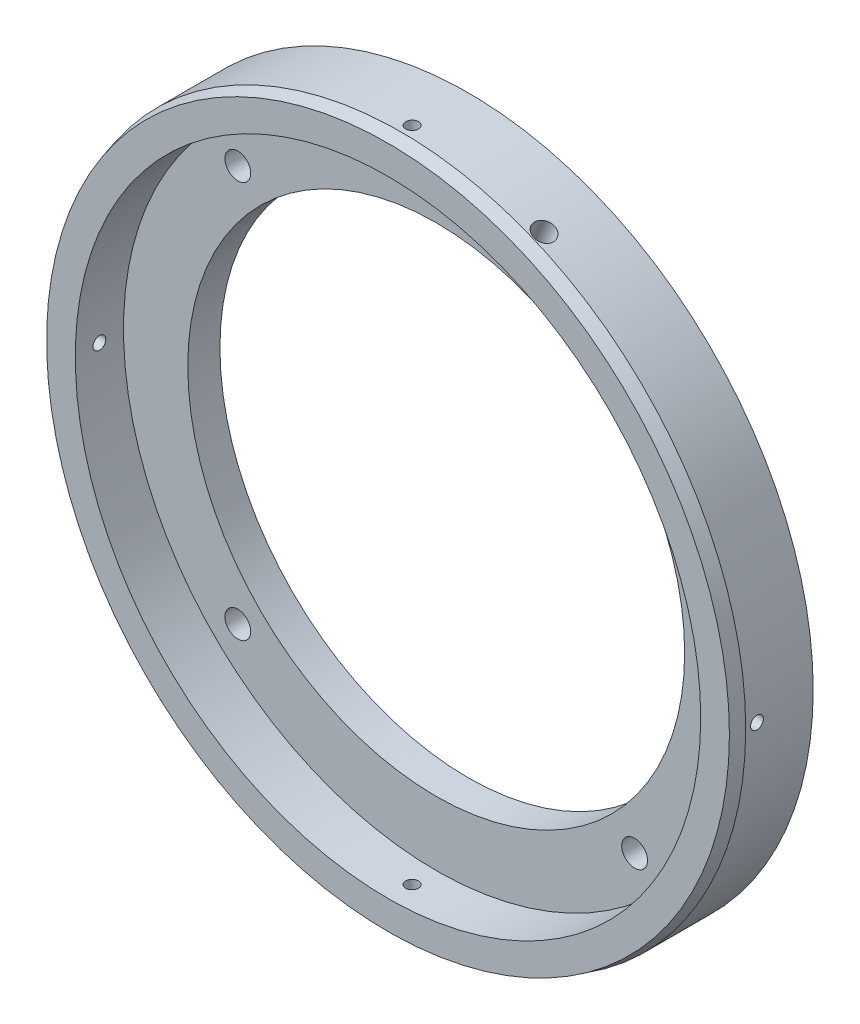
SolidWorks part; units mm, degrees
material "6061-T6 (SS)"
ref_plane "Front Plane" through (0, 0, 0) normal (0, 0, 1) x (1, 0, 0)
ref_plane "Top Plane" through (0, 0, 0) normal (0, 1, 0) x (1, 0, 0)
ref_plane "Right Plane" through (0, 0, 0) normal (1, 0, 0) x (0, 0, -1)
sketch "Sketch1" plane through (0, 0, 0) normal (0, 0, 1) x (1, 0, 0)
  circle A0 centre (0, 0) radius 68.1355
  circle A1 centre (0, 0) radius 49.0855
extrude "Extrude1" add sketch "Sketch1" along normal blind 15.875
sketch "Sketch2" plane through (0, 0, 15.875) normal (0, 0, 1) x (1, 0, 0)
  circle A0 centre (0, 0) radius 61.7855
extrude "Extrude2" cut sketch "Sketch2" against normal blind 9.525
ref_plane "Plane1" through (0, 0, 11.1125) normal (0, 0, 1) x (1, 0, 0)
sketch "Sketch3" plane through (0, 0, 11.1125) normal (0, 0, 1) x (1, 0, 0)
  line L0 (0, 0) -> (0, 68.1355) construction
  line L1 (0, 0) -> (26.0743, 62.949) construction
  circle A0 centre (0, 0) radius 68.1355 construction
  arc A1 (0, 68.1355) -> (26.0743, 62.949) centre (0, 0) cw
  circle A2 centre (0, 0) radius 55.4355
  arc A3 (0, 55.4355) -> (39.1988, 39.1988) centre (0, 0) cw
ref_plane "Plane3" through (26.0743, 62.949, 11.1125) normal (0.3827, 0.9239, 0) x (-0.9239, 0.3827, 0)
hole_wizard "#21 (0.159) Diameter Hole1" positions "Sketch7" profile "Sketch6" hole size "#21" standard "Ansi Inch"
sketch "Sketch7" plane through (26.0743, 62.949, 11.1125) normal (0.3827, 0.9239, 0) x (-0.9239, 0.3827, 0)
  point P1 (0, 0)
sketch "Sketch6" plane through (26.0743, 62.949, 11.1125) normal (0, 0, 1) x (-0.9239, 0.3827, 0)
  line L0 (0, 0) -> (0, 13.9133)
  line L1 (0, 13.9133) -> (2.0193, 12.7)
  line L2 (2.0193, 12.7) -> (2.0193, 0)
  line L5 (2.0193, 0) -> (0, 0)
  line L10 (0, 13.9133) -> (-2.0193, 12.7) construction
  line L11 (0, -6.35) -> (0, 107.95) construction
  dimension "Hole Dia." = 4.0386
  dimension "Hole Depth" = 12.7
  dimension "Drill Angle" = 118
ref_plane "Plane2" through (0, 68.1355, 11.1125) normal (0, 1, 0) x (-1, 0, 0)
hole_wizard "#39 (0.0995) Diameter Hole2" positions "Sketch5" profile "Sketch4" hole size "#39" standard "Ansi Inch"
sketch "Sketch5" plane through (0, 68.1355, 11.1125) normal (0, 1, 0) x (-1, 0, 0)
  point P1 (0, 0)
sketch "Sketch4" plane through (0, 68.1355, 11.1125) normal (1, 0, 0) x (0, 0, 1)
  line L0 (0, 0) -> (0, 13.4593)
  line L1 (0, 13.4593) -> (1.2636, 12.7)
  line L2 (1.2636, 12.7) -> (1.2636, 0)
  line L5 (1.2636, 0) -> (0, 0)
  line L10 (0, 13.4593) -> (-1.2637, 12.7) construction
  line L11 (0, -6.35) -> (0, 107.95) construction
  dimension "Hole Dia." = 2.5273
  dimension "Hole Depth" = 12.7
  dimension "Drill Angle" = 118
pattern_circular "CirPattern1" count 4 over 360 about axis through (0, 0, 15.875) along (0, 0, -1) of "#39 (0.0995) Diameter Hole2"
sketch "Sketch11" plane through (0, 0, 6.35) normal (0, 0, 1) x (1, 0, 0)
  arc A0 (39.1988, 39.1988) -> (46.0929, 30.7983) centre (0, 0) cw construction
  arc A1 (46.0929, 30.7983) -> (51.2157, 21.2142) centre (0, 0) cw construction
hole_wizard "#7 (0.201) Diameter Hole1" positions "Sketch9" profile "Sketch8" hole size "#7" standard "Ansi Inch"
sketch "Sketch9" plane through (0, 0, 11.1125) normal (0, 0, 1) x (1, 0, 0)
  point P1 (39.1988, 39.1988)
sketch "Sketch8" plane through (39.1988, 39.1988, 11.1125) normal (1, 0, 0) x (0, -1, 0)
  line L0 (0, 0) -> (0, 14.2338)
  line L1 (0, 14.2338) -> (2.5527, 12.7)
  line L2 (2.5527, 12.7) -> (2.5527, 0)
  line L5 (2.5527, 0) -> (0, 0)
  line L10 (0, 14.2338) -> (-2.5527, 12.7) construction
  line L11 (0, -6.35) -> (0, 107.95) construction
  dimension "Hole Dia." = 5.1054
  dimension "Hole Depth" = 12.7
  dimension "Drill Angle" = 118
pattern_circular "CirPattern2" count 4 over 360 about axis through (0, 0, 0) along (0, 0, 1) of "#7 (0.201) Diameter Hole1"
chamfer "Chamfer1" distance 2.54 angle 15 1 edges at (68.1355, 0, 15.875)
sketch "Sketch10" plane through (0, 0, 0) normal (0, 0, -1) x (-1, 0, 0)
  circle A0 centre (0, 0) radius 55.4355 construction
  point P0 (-39.1988, 39.1988)
  point P1 (39.1988, 39.1988)
  point P3 (39.1988, -39.1988)
  point P5 (-39.1988, -39.1988)
hole_wizard "1/4 (0.25) Diameter Hole1" [suppressed] positions "3DSketch1" profile "Sketch12" hole size "1/4" standard "Ansi Inch"
sketch3d "3DSketch1"
  point P0 (46.0929, 30.7983, 6.35)
sketch "Sketch12" plane through (46.0929, 30.7983, 6.35) normal (1, 0, 0) x (0, -1, 0)
  line L0 (0, 0) -> (0, 14.6077)
  line L1 (0, 14.6077) -> (3.175, 12.7)
  line L2 (3.175, 12.7) -> (3.175, 0)
  line L5 (3.175, 0) -> (0, 0)
  line L10 (0, 14.6077) -> (-3.175, 12.7) construction
  line L11 (0, -6.35) -> (0, 107.95) construction
  dimension "Hole Dia." = 6.35
  dimension "Hole Depth" = 12.7
  dimension "Drill Angle" = 118
hole_wizard "7/16 (0.4375) Diameter Hole1" [suppressed] positions "3DSketch2" profile "Sketch13" hole size "7/16" standard "Ansi Inch"
sketch3d "3DSketch2"
  point P0 (51.2157, 21.2142, 6.35)
sketch "Sketch13" plane through (51.2157, 21.2142, 6.35) normal (1, 0, 0) x (0, -1, 0)
  line L0 (0, 0) -> (0, 16.0385)
  line L1 (0, 16.0385) -> (5.5562, 12.7)
  line L2 (5.5562, 12.7) -> (5.5562, 0)
  line L5 (5.5562, 0) -> (0, 0)
  line L10 (0, 16.0385) -> (-5.5563, 12.7) construction
  line L11 (0, -6.35) -> (0, 107.95) construction
  dimension "Hole Dia." = 11.1125
  dimension "Hole Depth" = 12.7
  dimension "Drill Angle" = 118
sketch "Sketch15" [suppressed] plane through (0, 0, 6.35) normal (0, 0, 1) x (1, 0, 0)
  line L0 (43.453, 29.0344) -> (48.7328, 32.5622)
  line L1 (47.0709, 22.7043) -> (52.7904, 25.4631)
  arc A0 (43.453, 29.0344) -> (47.0709, 22.7043) centre (0, 0) cw
  circle A1 centre (46.0929, 30.7983) radius 3.175 construction
  arc A2 (48.7328, 32.5622) -> (52.7904, 25.4631) centre (0, 0) cw
extrude "Extrude3" [suppressed] cut sketch "Sketch15" against normal through all
pattern_circular "CirPattern3" [suppressed] count 4 over 360
sketch "Sketch16" [suppressed] plane through (0, 0, 0) normal (0, 0, -1) x (-1, 0, 0)
  point P0 (-46.0929, 30.7983)
  point P1 (30.7983, 46.0929)
  point P3 (46.0929, -30.7983)
  point P5 (-30.7983, -46.0929)
